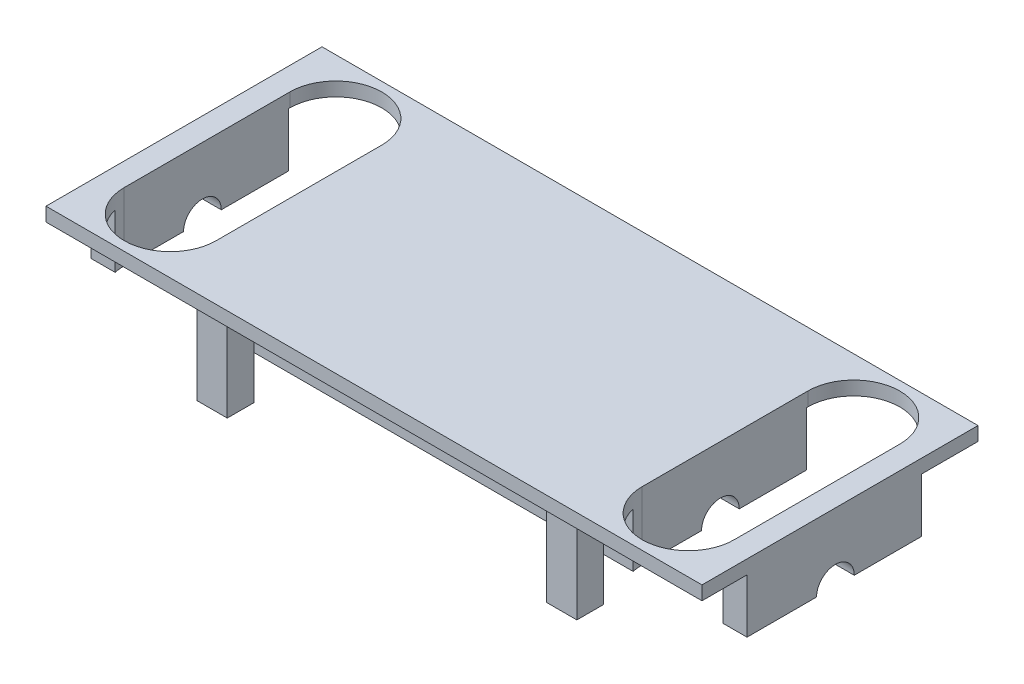
SolidWorks part; units mm, degrees
ref_plane "Front Plane" through (0, 0, 0) normal (0, 0, 1) x (1, 0, 0)
ref_plane "Top Plane" through (0, 0, 0) normal (0, 1, 0) x (1, 0, 0)
ref_plane "Right Plane" through (0, 0, 0) normal (1, 0, 0) x (0, 0, -1)
sketch "Sketch1" plane through (0, 0, 0) normal (0, 1, 0) x (1, 0, 0)
  line L0 (-5.842, 0) -> (-7.112, -1.2443)
  line L1 (-7.112, -1.2443) -> (-7.112, -8.6103)
  line L2 (-7.112, -8.6103) -> (1.27, -8.6103)
  line L3 (1.27, -8.6103) -> (1.27, -1.2443)
  line L4 (1.27, -1.2443) -> (0, 0)
  line L5 (0, 0) -> (-5.842, 0)
  line L6 (90.678, 0) -> (89.408, -1.2443)
  line L7 (89.408, -1.2443) -> (89.408, -8.6103)
  line L8 (89.408, -8.6103) -> (97.79, -8.6103)
  line L9 (97.79, -8.6103) -> (97.79, -1.2443)
  line L10 (97.79, -1.2443) -> (96.52, 0)
  line L11 (96.52, 0) -> (90.678, 0)
  point P2 (93.599, -8.6103)
  point P21 (-2.921, -8.6103)
  dimension "D1" = 7.366
  dimension "D2" = 8.382
  dimension "D3" = 1.778
  dimension "D4" = 5.842
  dimension "D5" = 96.52
extrude "Guide rods" add sketch "Sketch1" along normal blind 25.4
sketch "Sketch2" plane through (0, 25.4, 0) normal (0, 1, 0) x (1, 0, 0)
  line L0 (-7.112, -1.2443) -> (-7.112, -8.6103) construction
  line L1 (-45.212, -12.1663) -> (135.89, -12.1663)
  line L2 (-45.212, -12.1663) -> (-45.212, 64.0337)
  line L3 (-45.212, 64.0337) -> (135.89, 64.0337)
  line L4 (135.89, -12.1663) -> (135.89, 64.0337)
  line L5 (-7.112, -8.6103) -> (1.27, -8.6103) construction
  line L6 (97.79, -8.6103) -> (97.79, -1.2443) construction
  point P17 (-29.337, 17.386)
  point P27 (0, 0)
  dimension "D1" = 38.1
  dimension "D2" = 3.556
  dimension "D3" = 38.1
  dimension "D4" = 76.2
extrude "baseplate" add sketch "Sketch2" along normal blind 3.81
sketch "Sketch3" plane through (-45.212, 0, 0) normal (-1, 0, 0) x (0, 0, 1)
  line L0 (-48.3705, 25.4) -> (-0.2633, 25.4)
  line L2 (-0.2633, 25.4) -> (-0.2633, 10.4877)
  line L3 (-0.2633, 10.4877) -> (-19.4567, 10.4877)
  line L7 (-29.8707, 10.4877) -> (-48.3705, 10.4877)
  line L8 (-48.3705, 10.4877) -> (-48.3705, 25.4)
  line L9 (12.1663, 29.21) -> (12.1663, 25.4) construction
  line L10 (-64.0337, 25.4) -> (12.1663, 25.4) construction
  arc A0 (-19.4567, 10.4877) -> (-29.8707, 10.4877) centre (-24.6637, 10.4877) ccw
  point P9 (0, 0)
  point P12 (0, 0)
  dimension "D1" = 5.207
  dimension "D2" = 36.83
extrude "rod cup" add sketch "Sketch3" against normal up to surface (181.102 mm away) up to face at (135.89, 27.305, -25.9337)
sketch "Sketch4" plane through (0, 29.21, 0) normal (0, 1, 0) x (1, 0, 0)
  line L0 (-26.162, 48.7937) -> (-26.162, 3.0737) construction
  line L1 (-13.462, 48.7937) -> (-13.462, 3.0737)
  line L2 (-38.862, 48.7937) -> (-38.862, 3.0737)
  line L3 (-45.212, 64.0337) -> (-45.212, -12.1663) construction
  line L5 (-45.212, -12.1663) -> (135.89, -12.1663) construction
  line L6 (135.89, 64.0337) -> (-45.212, 64.0337) construction
  line L7 (45.339, 64.0337) -> (45.339, -12.1663) construction
  line L8 (116.84, 48.7937) -> (116.84, 3.0737) construction
  line L9 (104.14, 48.7937) -> (104.14, 3.0737)
  line L10 (129.54, 48.7937) -> (129.54, 3.0737)
  arc A0 (-13.462, 48.7937) -> (-38.862, 48.7937) centre (-26.162, 48.7937) ccw
  arc A1 (-38.862, 3.0737) -> (-13.462, 3.0737) centre (-26.162, 3.0737) ccw
  arc A2 (104.14, 48.7937) -> (129.54, 48.7937) centre (116.84, 48.7937) cw
  arc A3 (129.54, 3.0737) -> (104.14, 3.0737) centre (116.84, 3.0737) cw
  point P2 (-26.162, 25.9337)
  point P17 (116.84, 25.9337)
  dimension "D1" = 15.24
  dimension "D2" = 25.4
  dimension "D3" = 6.35
  dimension "D4" = 15.24
extrude "Handles" cut sketch "Sketch4" against normal through all
